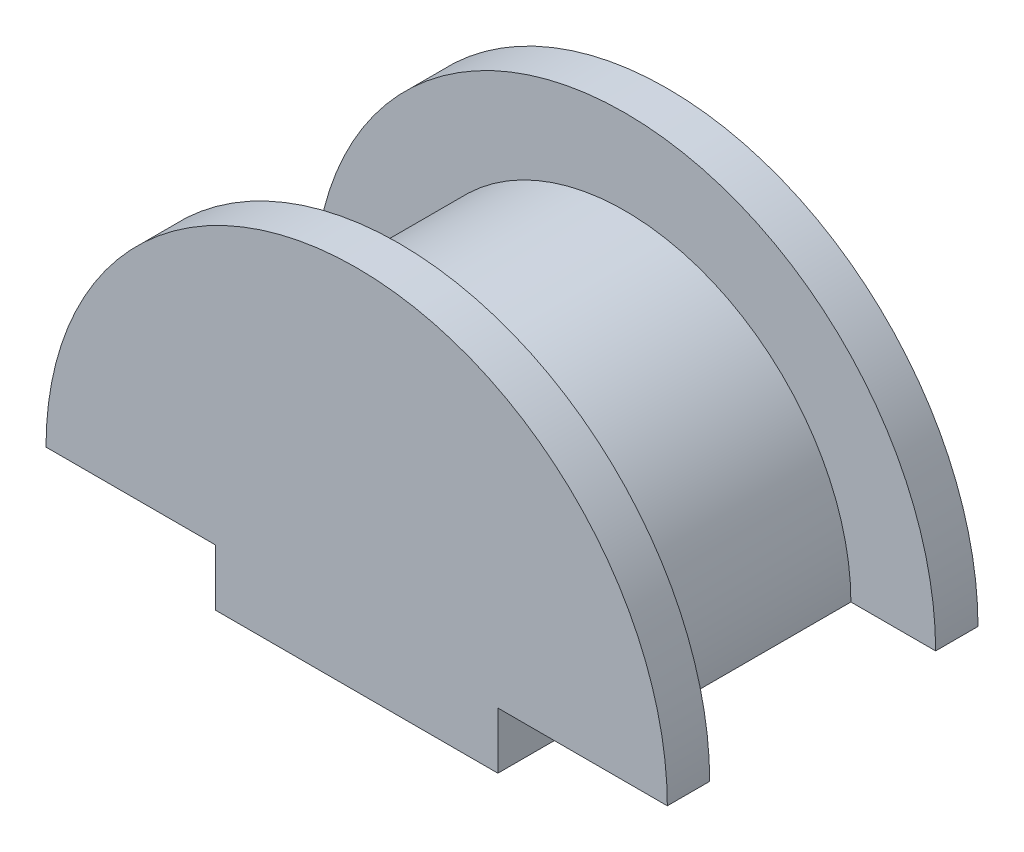
SolidWorks part; units mm, degrees
ref_plane "Alzado" through (0, 0, 0) normal (0, 0, 1) x (1, 0, 0)
ref_plane "Planta" through (0, 0, 0) normal (0, 1, 0) x (1, 0, 0)
ref_plane "Vista lateral" through (0, 0, 0) normal (1, 0, 0) x (0, 0, -1)
sketch "Croquis1" plane through (0, 0, 0) normal (0, 0, 1) x (1, 0, 0)
  line L0 (8, 0) -> (-8, 0)
  line L1 (0, 0) -> (0, 8) construction
  line L2 (5, 0) -> (5, -2)
  line L3 (5, 0) -> (-5, 0)
  line L4 (0, 0) -> (0, -2)
  line L5 (5, -2) -> (-5, -2)
  line L6 (-5, 0) -> (-5, -2)
  arc A0 (8, 0) -> (-8, 0) centre (0, 0) ccw
  dimension "D1" = 16
  dimension "D2" = 2
  dimension "D3" = 5
extrude "Saliente-Extruir1" add sketch "Croquis1" along normal mid plane 8 contours L3 L1 A0 L0 | L1 L0 A0 | L5 L2 L0 L4 | L3 L6 L5 L4
sketch "Croquis2" plane through (0, -2, 0) normal (0, -1, 0) x (1, 0, 0)
  circle A0 centre (0, 0) radius 3
  dimension "D1" = 6
extrude "Cortar-Extruir1" cut sketch "Croquis2" against normal blind 6
sketch "Croquis3" plane through (0, 0, 4) normal (0, 0, 1) x (1, 0, 0)
  line L5 (-5, -2) -> (5, -2)
  line L6 (5, -2) -> (5, 0)
  line L7 (5, 0) -> (8, 0)
  line L8 (-8, 0) -> (-5, 0)
  line L9 (-5, 0) -> (-5, -2)
  line L10 (-5, -2) -> (5, -2)
  line L11 (5, -2) -> (5, 0)
  line L12 (5, 0) -> (8, 0)
  line L13 (-8, 0) -> (-5, 0)
  line L14 (-5, 0) -> (-5, -2)
  line L15 (-8, 0) -> (-11, 0)
  line L16 (8, 0) -> (11, 0)
  line L17 (-11, 0) -> (-8, 0)
  line L18 (8, -3) -> (10.583, -3) construction
  line L19 (8, -5) -> (8, -3) construction
  line L20 (-8, -5) -> (8, -5) construction
  line L21 (-8, -3) -> (-8, -5) construction
  line L22 (-10.583, -3) -> (-8, -3) construction
  arc A0 (11, 0) -> (-11, 0) centre (0, 0) ccw
  arc A1 (8, 0) -> (-8, 0) centre (0, 0) ccw
  arc A3 (10.583, -3) -> (-10.583, -3) centre (0, 0) ccw construction
  arc A4 (8, 0) -> (-8, 0) centre (0, 0) ccw construction
  line M13 (-5, -2) -> (5, -2)
  line M14 (5, -2) -> (5, 0)
  line M15 (5, 0) -> (8, 0)
  arc M16 (8, 0) -> (-8, 0) centre (0, 0) ccw
  line M17 (-8, 0) -> (-5, 0)
  line M18 (-5, 0) -> (-5, -2)
  dimension "D1" = 0
  dimension "D2" = 3
extrude "Saliente-Extruir2" add sketch "Croquis3" along normal blind 1.5 contours L16 A0 L15 M16 | M18 M13 M14 M15 M16 M17
mirror "Simetría1" about plane through (0, 0, 0) normal (0, 0, 1) of "Saliente-Extruir2"
